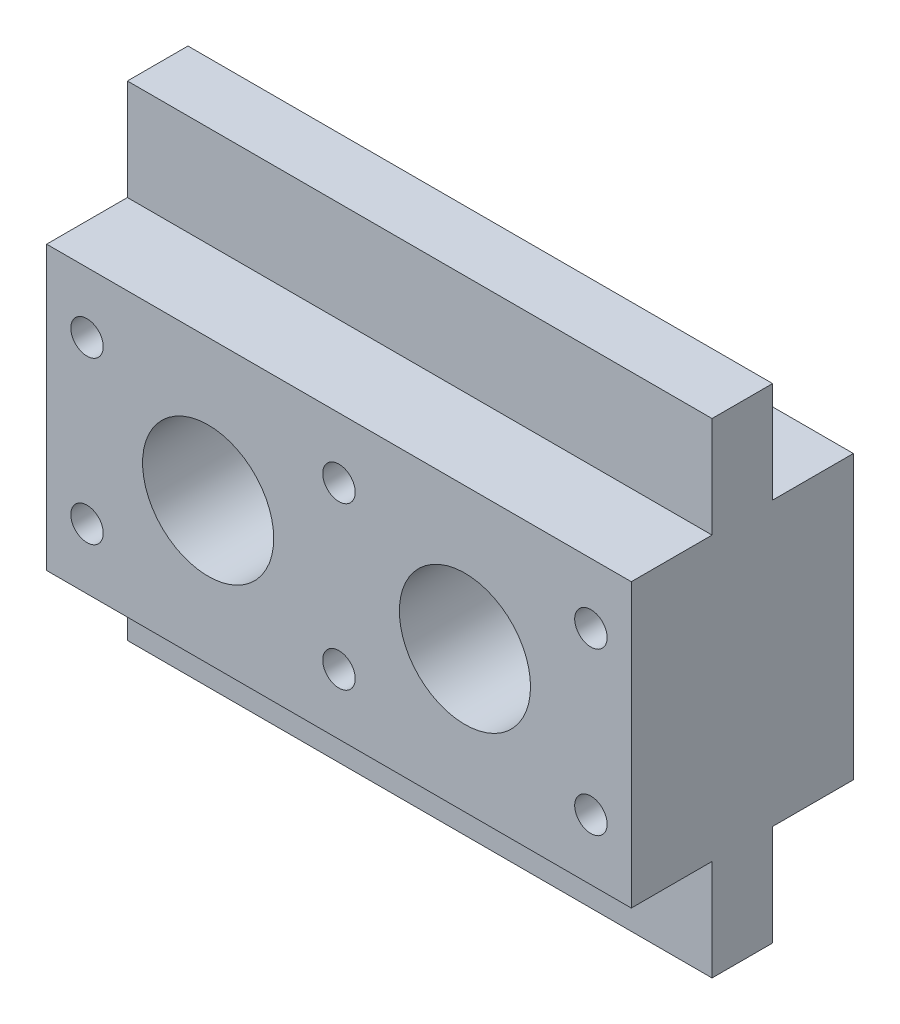
SolidWorks part; units mm, degrees
ref_plane "Front Plane" through (0, 0, 0) normal (0, 0, 1) x (1, 0, 0)
ref_plane "Top Plane" through (0, 0, 0) normal (0, 1, 0) x (1, 0, 0)
ref_plane "Right Plane" through (0, 0, 0) normal (1, 0, 0) x (0, 0, -1)
sketch "Sketch1" plane through (0, 0, 0) normal (0, 0, 1) x (1, 0, 0)
  line L1 (0, 0) -> (91.948, 0)
  line L2 (0, 0) -> (0, 76.2)
  line L3 (0, 76.2) -> (91.948, 76.2)
  line L4 (91.948, 0) -> (91.948, 76.2)
  dimension "D1" = 91.948
  dimension "D2" = 76.2
extrude "Boss-Extrude1" add sketch "Sketch1" along normal blind 4.7625
sketch "Sketch2" plane through (0, 0, 0) normal (0, 0, -1) x (-1, 0, 0)
  line L1 (0, 15.875) -> (-91.948, 15.875)
  line L2 (0, 15.875) -> (0, 60.325)
  line L3 (0, 60.325) -> (-91.948, 60.325)
  line L4 (-91.948, 15.875) -> (-91.948, 60.325)
  line L6 (0, 76.2) -> (0, 0) construction
  line L7 (-91.948, 0) -> (-91.948, 76.2) construction
  point P4 (0, 38.1)
  point P7 (-91.948, 38.1)
  point P10 (0, 38.1)
  point P13 (-91.948, 38.1)
  dimension "D1" = 44.45
extrude "Boss-Extrude2" add sketch "Sketch2" against normal blind 12.7 from surface at -4.7625 starting at face at (45.974, 38.1, 4.7625)
mirror "Mirror1" about plane through (0, 0, 0) normal (0, 0, 1) of "Boss-Extrude1", "Boss-Extrude2"
sketch "Sketch3" plane through (0, 0, 17.4625) normal (0, 0, 1) x (1, 0, 0)
  line L0 (0, 38.1) -> (91.948, 38.1) construction
  line L1 (0, 60.325) -> (0, 15.875) construction
  line L2 (91.948, 15.875) -> (91.948, 60.325) construction
  line L3 (45.974, 60.325) -> (45.974, 15.875) construction
  line L4 (91.948, 60.325) -> (0, 60.325) construction
  line L5 (0, 15.875) -> (91.948, 15.875) construction
  line L6 (0, 50.8) -> (91.948, 50.8) construction
  line L7 (0, 60.325) -> (0, 50.8) construction
  line L8 (6.35, 60.325) -> (6.35, 15.875) construction
  line L9 (0, 25.4) -> (91.948, 25.4) construction
  line L10 (0, 25.4) -> (0, 15.875) construction
  line L11 (0, 15.875) -> (91.948, 15.875) construction
  line L12 (6.35, 60.325) -> (0, 60.325) construction
  line L13 (91.948, 62.3141) -> (91.948, 12.3692) construction
  line L14 (91.948, 62.3141) -> (85.598, 62.3141) construction
  line L15 (85.598, 62.3141) -> (85.598, 12.3692) construction
  circle A0 centre (6.35, 50.8) radius 2.5527
  circle A1 centre (6.35, 25.4) radius 2.5527
  circle A2 centre (45.974, 25.4) radius 2.5527
  circle A3 centre (45.974, 50.8) radius 2.5527
  circle A4 centre (85.598, 50.8) radius 2.5527
  circle A5 centre (85.598, 25.4) radius 2.5527
  circle A6 centre (25.4, 38.1) radius 10.3124
  circle A7 centre (65.786, 38.1) radius 10.3124
  dimension "D5" = 5.1054
  dimension "D6" = 19.05
  dimension "D8" = 20.6248
  dimension "D9" = 20.6248
  dimension "D1" = 9.525
  dimension "D2" = 9.525
  dimension "D3" = 6.35
  dimension "D4" = 6.35
  dimension "D7" = 59.436
sketch "Sketch4" plane through (0, 0, 17.4625) normal (0, 0, 1) x (1, 0, 0)
  line L0 (0, 38.1) -> (91.948, 38.1) construction
  line L1 (45.974, 60.325) -> (45.974, 15.875) construction
  line L2 (0, 50.8) -> (91.948, 50.8) construction
  line L3 (6.35, 60.325) -> (6.35, 15.875) construction
  line L4 (0, 25.4) -> (91.948, 25.4) construction
  line L5 (6.35, 60.325) -> (0, 60.325) construction
  line L6 (91.948, 62.3141) -> (85.598, 62.3141) construction
  line L7 (85.598, 62.3141) -> (85.598, 12.3692) construction
  circle A0 centre (6.35, 50.8) radius 2.5527
  circle A1 centre (6.35, 25.4) radius 2.5527
  circle A2 centre (45.974, 25.4) radius 2.5527
  circle A3 centre (45.974, 50.8) radius 2.5527
  circle A4 centre (85.598, 50.8) radius 2.5527
  circle A5 centre (85.598, 25.4) radius 2.5527
extrude "Cut-Extrude6" cut sketch "Sketch3" against normal through all contours A6 | A7
extrude "Cut-Extrude7" cut sketch "Sketch4" against normal blind 12.7 contours A1 | A0 | A2 | A5 | A4 | A3
